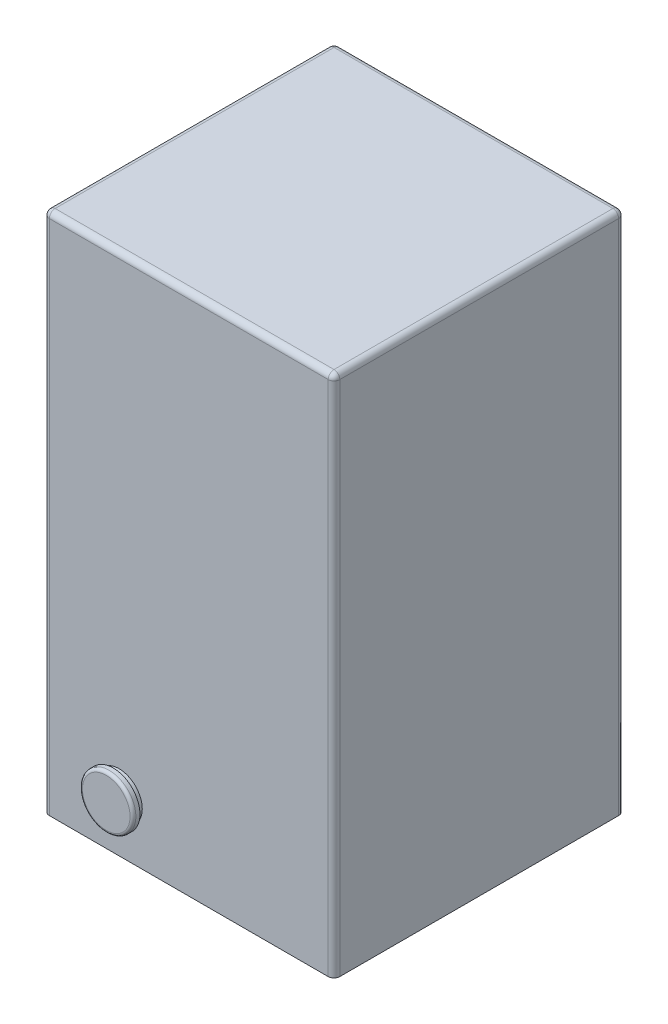
SolidWorks part; units mm, degrees
ref_plane "Alzado" through (0, 0, 0) normal (0, 0, 1) x (1, 0, 0)
ref_plane "Planta" through (0, 0, 0) normal (0, 1, 0) x (1, 0, 0)
ref_plane "Vista lateral" through (0, 0, 0) normal (1, 0, 0) x (0, 0, -1)
sketch "Croquis1" plane through (0, 0, 0) normal (0, 0, 1) x (1, 0, 0)
  line L1 (0, 0) -> (500, 0)
  line L2 (0, 0) -> (0, -900)
  line L3 (0, -900) -> (500, -900)
  line L4 (500, 0) -> (500, -900)
  dimension "D1" = 900
  dimension "D2" = 500
extrude "Saliente-Extruir1" add sketch "Croquis1" along normal blind 500
fillet "Redondeo1" radius 10 8 edges at (0, -450, 0) (250, 0, 0) (500, -450, 0) (0, 0, 250) (0, -450, 500) (250, 0, 500) (500, 0, 250) (500, -450, 500)
sketch "Croquis2" plane through (0, 0, 500) normal (0, 0, 1) x (1, 0, 0)
  line L0 (10, -10) -> (10, -900) construction
  line L1 (10, -900) -> (490, -900) construction
  circle A0 centre (130, -810) radius 40
  dimension "D1" = 80
  dimension "D2" = 120
  dimension "D3" = 90
extrude "Saliente-Extruir2" add sketch "Croquis2" along normal blind 22
sketch "Croquis3" plane through (0, 0, 522) normal (0, 0, 1) x (1, 0, 0)
  circle A0 centre (130, -810) radius 46
  dimension "D1" = 92
extrude "Saliente-Extruir3" add sketch "Croquis3" against normal blind 12
fillet "Redondeo2" radius 5 1 edges at (176, -810, 522)
